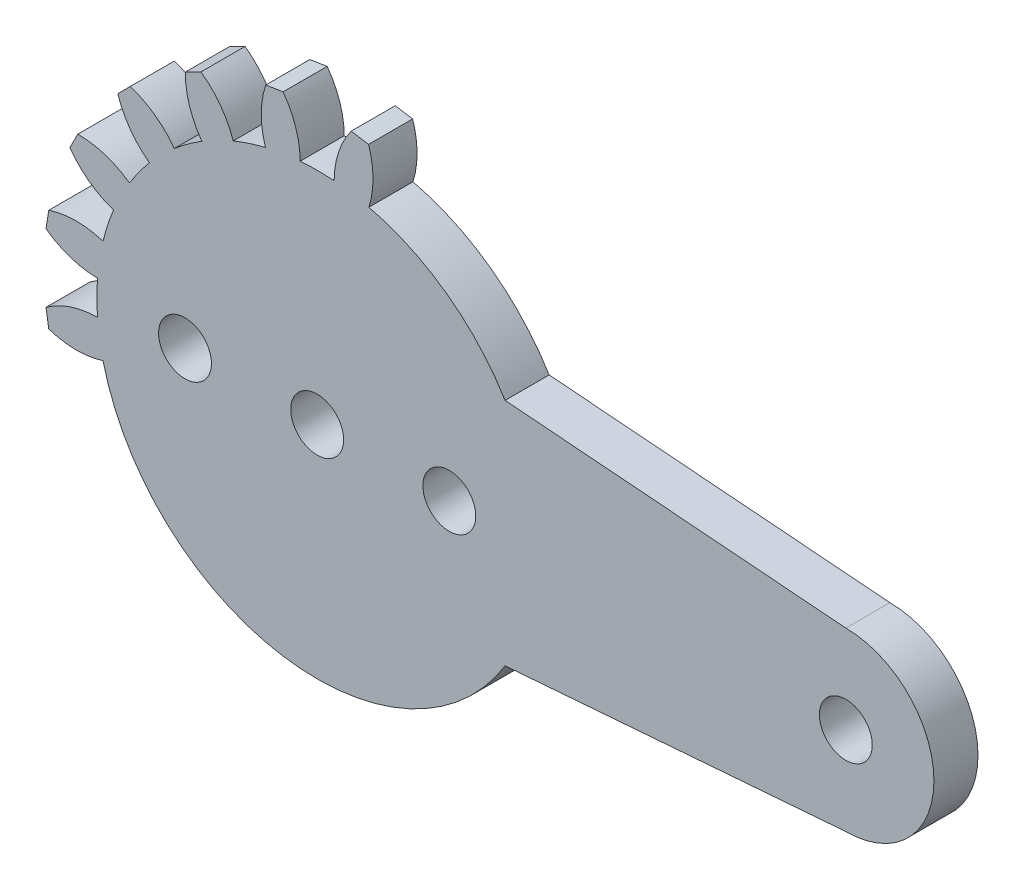
SolidWorks part; units mm, degrees
ref_plane "Front Plane" through (0, 0, 0) normal (0, 0, 1) x (1, 0, 0)
ref_plane "Top Plane" through (0, 0, 0) normal (0, 1, 0) x (1, 0, 0)
ref_plane "Right Plane" through (0, 0, 0) normal (1, 0, 0) x (0, 0, -1)
sketch "Sketch1" plane through (0, 0, 0) normal (0, 0, 1) x (1, 0, 0)
  line L0 (0, 0) -> (30, 0) construction
  line L1 (30, 5) -> (10.6638, 6.5218)
  line L2 (10.6638, 6.5218) -> (-2.4545, 7.5542) construction
  line L3 (-9.5123, 8.1097) -> (-9.5263, 8.1108) construction
  line L4 (30, -5) -> (10.6638, -6.5218)
  line L5 (0, 0) -> (-12.5, 0) construction
  line L6 (0, 0) -> (0, -12.5) construction
  line L7 (0, 0) -> (-4.7898, 14.7414) construction
  line L8 (0, 0) -> (0, 14) construction
  line L9 (0, 0) -> (-2.4247, 15.3092) construction
  line L10 (-2.9186, 15.231) -> (-1.9309, 15.3874)
  line L11 (1.9309, 15.3874) -> (2.9186, 15.231)
  line L12 (6.5913, 14.0376) -> (7.4824, 13.5836) [skipped]
  line L13 (10.6066, 11.3137) -> (11.3137, 10.6066) [skipped]
  line L14 (13.5836, 7.4824) -> (14.0376, 6.5913) [skipped]
  line L15 (15.231, 2.9186) -> (15.3874, 1.9309) [skipped]
  line L16 (15.3874, -1.9309) -> (15.231, -2.9186) [skipped]
  line L17 (14.0376, -6.5913) -> (13.5836, -7.4824) [skipped]
  line L18 (11.3137, -10.6066) -> (10.6066, -11.3137) [skipped]
  line L19 (7.4824, -13.5836) -> (6.5913, -14.0376) [skipped]
  line L20 (2.9186, -15.231) -> (1.9309, -15.3874) [skipped]
  line L21 (-1.9309, -15.3874) -> (-2.9186, -15.231) [skipped]
  line L22 (-6.5913, -14.0376) -> (-7.4824, -13.5836) [skipped]
  line L23 (-10.6066, -11.3137) -> (-11.3137, -10.6066) [skipped]
  line L24 (-13.5836, -7.4824) -> (-14.0376, -6.5913) [skipped]
  line L25 (-15.231, -2.9186) -> (-15.3874, -1.9309)
  line L26 (-15.3874, 1.9309) -> (-15.231, 2.9186)
  line L27 (-14.0376, 6.5913) -> (-13.5836, 7.4824)
  line L28 (-11.3137, 10.6066) -> (-10.6066, 11.3137)
  line L29 (-7.4824, 13.5836) -> (-6.5913, 14.0376)
  line L30 (-2.4545, 7.5542) -> (-9.5123, 8.1097) construction
  line L31 (-9.5263, 8.1108) -> (-11.3101, 8.2512) construction
  line L32 (-11.3101, 8.2512) -> (-26.6541, 9.4588) construction
  arc A0 (-12.1503, -2.9361) -> (10.6638, -6.5218) centre (0, 0) ccw
  circle A1 centre (30, 0) radius 1.5
  circle A2 centre (0, 0) radius 1.5
  arc A3 (30, -5) -> (30, 5) centre (30, 0) ccw
  circle A4 centre (-7.5, 0) radius 1.5
  circle A5 centre (7.5, 0) radius 1.5
  arc A6 (-15.3799, -1.9254) -> (-15.3799, 1.9254) centre (0, 0) ccw construction
  arc A7 (-10.5802, 9.1684) -> (-11.3101, 8.2512) centre (0, 0) ccw construction
  arc A8 (-2.9361, 12.1503) -> (-2.9186, 15.231) centre (1.8294, 13.6636) cw
  arc A9 (-0.9623, 12.4629) -> (-1.9309, 15.3874) centre (-5.9622, 12.4295) ccw
  arc A10 (2.9361, 12.1503) -> (2.9186, 15.231) centre (-1.8294, 13.6636) ccw
  arc A11 (0.9623, 12.4629) -> (1.9309, 15.3874) centre (5.9622, 12.4295) cw
  arc A12 (6.547, 10.6483) -> (7.4824, 13.5836) centre (2.4824, 13.5602) ccw [skipped]
  arc A13 (4.7664, 11.5556) -> (6.5913, 14.0376) centre (9.5113, 9.9788) cw [skipped]
  arc A14 (9.5171, 8.104) -> (11.3137, 10.6066) centre (6.5512, 12.1294) ccw [skipped]
  arc A15 (8.104, 9.5171) -> (10.6066, 11.3137) centre (12.1294, 6.5512) cw [skipped]
  arc A16 (11.5556, 4.7664) -> (14.0376, 6.5913) centre (9.9788, 9.5113) ccw [skipped]
  arc A17 (10.6483, 6.547) -> (13.5836, 7.4824) centre (13.5602, 2.4824) cw [skipped]
  arc A18 (12.4629, 0.9623) -> (15.3874, 1.9309) centre (12.4295, 5.9622) ccw [skipped]
  arc A19 (12.1503, 2.9361) -> (15.231, 2.9186) centre (13.6636, -1.8294) cw [skipped]
  arc A20 (12.1503, -2.9361) -> (15.231, -2.9186) centre (13.6636, 1.8294) ccw [skipped]
  arc A21 (12.4629, -0.9623) -> (15.3874, -1.9309) centre (12.4295, -5.9622) cw [skipped]
  arc A22 (10.6483, -6.547) -> (13.5836, -7.4824) centre (13.5602, -2.4824) ccw [skipped]
  arc A23 (11.5556, -4.7664) -> (14.0376, -6.5913) centre (9.9788, -9.5113) cw [skipped]
  arc A24 (8.104, -9.5171) -> (10.6066, -11.3137) centre (12.1294, -6.5512) ccw [skipped]
  arc A25 (9.5171, -8.104) -> (11.3137, -10.6066) centre (6.5512, -12.1294) cw [skipped]
  arc A26 (4.7664, -11.5556) -> (6.5913, -14.0376) centre (9.5113, -9.9788) ccw [skipped]
  arc A27 (6.547, -10.6483) -> (7.4824, -13.5836) centre (2.4824, -13.5602) cw [skipped]
  arc A28 (0.9623, -12.4629) -> (1.9309, -15.3874) centre (5.9622, -12.4295) ccw [skipped]
  arc A29 (2.9361, -12.1503) -> (2.9186, -15.231) centre (-1.8294, -13.6636) cw [skipped]
  arc A30 (-2.9361, -12.1503) -> (-2.9186, -15.231) centre (1.8294, -13.6636) ccw [skipped]
  arc A31 (-0.9623, -12.4629) -> (-1.9309, -15.3874) centre (-5.9622, -12.4295) cw [skipped]
  arc A32 (-6.547, -10.6483) -> (-7.4824, -13.5836) centre (-2.4824, -13.5602) ccw [skipped]
  arc A33 (-4.7664, -11.5556) -> (-6.5913, -14.0376) centre (-9.5113, -9.9788) cw [skipped]
  arc A34 (-9.5171, -8.104) -> (-11.3137, -10.6066) centre (-6.5512, -12.1294) ccw [skipped]
  arc A35 (-8.104, -9.5171) -> (-10.6066, -11.3137) centre (-12.1294, -6.5512) cw [skipped]
  arc A36 (-11.5556, -4.7664) -> (-14.0376, -6.5913) centre (-9.9788, -9.5113) ccw [skipped]
  arc A37 (-10.6483, -6.547) -> (-13.5836, -7.4824) centre (-13.5602, -2.4824) cw [skipped]
  arc A38 (-12.4629, -0.9623) -> (-15.3874, -1.9309) centre (-12.4295, -5.9622) ccw
  arc A39 (-12.1503, -2.9361) -> (-15.231, -2.9186) centre (-13.6636, 1.8294) cw
  arc A40 (-12.1503, 2.9361) -> (-15.231, 2.9186) centre (-13.6636, -1.8294) ccw
  arc A41 (-12.4629, 0.9623) -> (-15.3874, 1.9309) centre (-12.4295, 5.9622) cw
  arc A42 (-10.6483, 6.547) -> (-13.5836, 7.4824) centre (-13.5602, 2.4824) ccw
  arc A43 (-11.5556, 4.7664) -> (-14.0376, 6.5913) centre (-9.9788, 9.5113) cw
  arc A44 (-8.104, 9.5171) -> (-10.6066, 11.3137) centre (-12.1294, 6.5512) ccw
  arc A45 (-9.5171, 8.104) -> (-11.3137, 10.6066) centre (-6.5512, 12.1294) cw
  arc A46 (-4.7664, 11.5556) -> (-6.5913, 14.0376) centre (-9.5113, 9.9788) ccw
  arc A47 (-6.547, 10.6483) -> (-7.4824, 13.5836) centre (-2.4824, 13.5602) cw
  arc A48 (-12.4629, -0.9623) -> (-12.1503, -2.9361) centre (0, 0) ccw construction
  arc A49 (-12.1503, 2.9361) -> (-12.4629, 0.9623) centre (0, 0) ccw construction
  arc A50 (-12.4629, 0.9623) -> (-12.4629, -0.9623) centre (0, 0) ccw
  arc A51 (-10.6483, 6.547) -> (-11.5556, 4.7664) centre (0, 0) ccw construction
  arc A52 (-11.5556, 4.7664) -> (-12.1503, 2.9361) centre (0, 0) ccw
  arc A53 (-8.104, 9.5171) -> (-9.5123, 8.1097) centre (0, 0) ccw construction
  arc A54 (-9.5171, 8.104) -> (-10.6483, 6.547) centre (0, 0) ccw
  arc A55 (-4.7664, 11.5556) -> (-6.547, 10.6483) centre (0, 0) ccw construction
  arc A56 (-6.547, 10.6483) -> (-8.104, 9.5171) centre (0, 0) ccw
  arc A57 (-1.9554, 12.3461) -> (-2.9361, 12.1503) centre (0, 0) ccw construction
  arc A58 (-2.9361, 12.1503) -> (-4.7664, 11.5556) centre (0, 0) ccw
  arc A59 (2.9361, 12.1503) -> (0.9623, 12.4629) centre (0, 0) ccw construction
  arc A60 (0.9623, 12.4629) -> (-0.9623, 12.4629) centre (0, 0) ccw
  arc A61 (-7.2292, 11.9891) -> (-9.1684, 10.5802) centre (0, 0) ccw construction
  arc A62 (-9.1684, 10.5802) -> (-10.5802, 9.1684) centre (0, 0) ccw construction
  arc A63 (-11.3101, 8.2512) -> (-11.9891, 7.2292) centre (0, 0) ccw construction
  arc A64 (-13.6363, 3.1705) -> (-13.9486, 1.1985) centre (0, 0) ccw construction
  arc A65 (-11.9891, 7.2292) -> (-12.8956, 5.4502) centre (0, 0) ccw construction
  arc A66 (-13.9486, 1.1985) -> (-13.9486, -1.1985) centre (0, 0) ccw construction
  arc A67 (-13.9486, -1.1985) -> (-13.6363, -3.1705) centre (0, 0) ccw construction
  arc A68 (-15.3799, 1.9254) -> (-15.3799, -1.9254) centre (0, 0) ccw construction
  arc A69 (-13.6363, -3.1705) -> (12.4616, -6.3803) centre (0, 0) ccw construction
  arc A70 (-2.1901, 13.8276) -> (-3.1705, 13.6363) centre (0, 0) ccw construction
  arc A71 (12.4616, -6.3803) -> (14, 0) centre (0, 0) ccw construction
  arc A72 (10.6638, -6.5218) -> (12.5, 0) centre (0, 0) ccw construction
  arc A73 (10.6638, 6.5218) -> (2.9361, 12.1503) centre (0, 0) ccw
  arc A74 (14, 0) -> (12.4616, 6.3803) centre (0, 0) ccw construction
  arc A75 (12.4616, 6.3803) -> (3.1705, 13.6363) centre (0, 0) ccw construction
  arc A76 (3.1705, 13.6363) -> (1.1985, 13.9486) centre (0, 0) ccw construction
  arc A77 (1.1985, 13.9486) -> (0, 14) centre (0, 0) ccw construction
  arc A78 (0, 14) -> (-1.1985, 13.9486) centre (0, 0) ccw construction
  arc A79 (-1.1985, 13.9486) -> (-2.1901, 13.8276) centre (0, 0) ccw construction
  arc A80 (-0.9623, 12.4629) -> (-1.9554, 12.3461) centre (0, 0) ccw construction
  arc A81 (-3.1705, 13.6363) -> (-4.3262, 13.3148) centre (0, 0) ccw construction
  arc A82 (-5.4502, 12.8956) -> (-7.2292, 11.9891) centre (0, 0) ccw construction
  arc A83 (-4.3262, 13.3148) -> (-5.4502, 12.8956) centre (0, 0) ccw construction
  arc A84 (12.5, 0) -> (10.6638, 6.5218) centre (0, 0) ccw construction
  arc A85 (-9.5123, 8.1097) -> (-9.5171, 8.104) centre (0, 0) ccw construction
  arc A86 (-12.8956, 5.4502) -> (-13.6363, 3.1705) centre (0, 0) ccw construction
  arc A87 (25, 0) -> (30, -5) centre (30, 0) ccw construction
  arc A88 (30, 5) -> (25, 0) centre (30, 0) ccw construction
  point P21 (-1.9554, 12.3461)
  point P27 (-2.4247, 15.3092)
  point P149 (0, 0)
  dimension "D1" = 25
  dimension "D2" = 3
  dimension "D3" = 10
  dimension "D5" = 3
  dimension "D7" = 31
  dimension "D8" = 28
  dimension "D13" = 5
  dimension "30" = 30
  dimension "D4" = 4.5
  dimension "D6" = 7.5
  dimension "D9" = 18
  dimension "D10" = 9
  dimension "D11" = 1
  dimension "D12" = 1
  dimension "D14" = 20
extrude "Boss-Extrude1" add sketch "Sketch1" along normal blind 2.5
